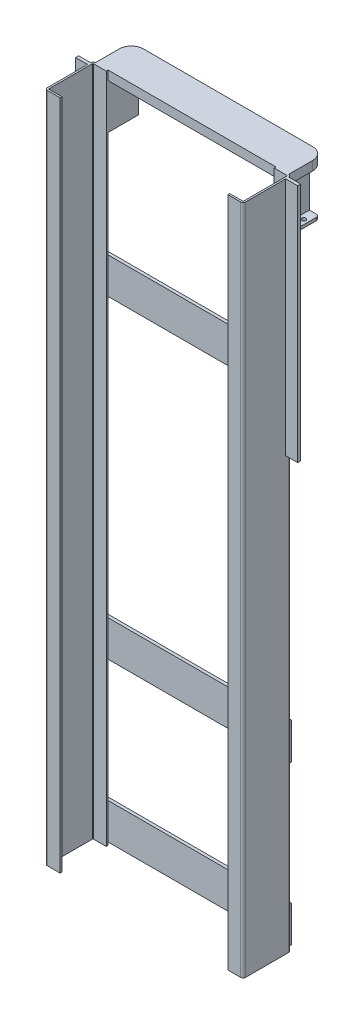
SolidWorks part; units mm, degrees
ref_plane "Front Plane" through (0, 0, 0) normal (0, 0, 1) x (1, 0, 0)
ref_plane "Top Plane" through (0, 0, 0) normal (0, 1, 0) x (1, 0, 0)
ref_plane "Right Plane" through (0, 0, 0) normal (1, 0, 0) x (0, 0, -1)
sketch "Sketch1" plane through (0, 0, 0) normal (0, 1, 0) x (1, 0, 0)
  line L0 (0, 0) -> (413, 0) construction
  line L1 (350, 100) -> (403, 100)
  line L2 (413, 90) -> (413, -90)
  line L3 (403, -100) -> (350, -100)
  arc A0 (413, -90) -> (403, -100) centre (403, -90) cw
  arc A1 (403, 100) -> (413, 90) centre (403, 90) cw
  point P9 (413, -100)
  point P12 (413, 100)
  dimension "D4" = 10
  dimension "D1" = 413
  dimension "D2" = 200
  dimension "D3" = 63
extrude "Extrude-Thin1" add sketch "Sketch1" along normal mid plane 2800 thin
sketch "Sketch2" plane through (0, 1400, 0) normal (0, 1, 0) x (1, 0, 0)
  line L1 (413, 90) -> (463, 90)
  line L2 (413, 90) -> (413, 77.5)
  line L3 (413, 77.5) -> (463, 77.5)
  line L4 (463, 90) -> (463, 77.5)
  dimension "D1" = 50
  dimension "D2" = 12.5
extrude "Boss-Extrude1" add sketch "Sketch2" against normal blind 1000
mirror "Mirror1" about plane through (0, 0, 0) normal (1, 0, 0) of bodies 102
sketch "Sketch4" plane through (0, 1400, 0) normal (0, 1, 0) x (1, 0, 0)
  line L1 (-403, 100) -> (403, 100)
  line L2 (-403, 100) -> (-403, 200)
  line L3 (-353, 250) -> (353, 250)
  line L4 (403, 100) -> (403, 200)
  arc A0 (-403, 200) -> (-353, 250) centre (-353, 200) cw
  arc A1 (353, 250) -> (403, 200) centre (353, 200) cw
  point P9 (403, 250)
  dimension "D2" = 50
  dimension "D1" = 150
extrude "Boss-Extrude2" add sketch "Sketch4" against normal blind 38
sketch "Sketch5" plane through (0, 0, -100) normal (0, 0, -1) x (-1, 0, 0)
  line L0 (-403, 1362) -> (-403, -1400) construction
  line L1 (-403, -1387.5) -> (403, -1387.5)
  line L2 (-403, -1387.5) -> (-403, -1237.5)
  line L3 (-403, -1237.5) -> (403, -1237.5)
  line L4 (403, -1387.5) -> (403, -1237.5)
  line L5 (403, 1362) -> (403, -1400) construction
  line L6 (350, -1400) -> (403, -1400) construction
  dimension "D1" = 12.5
  dimension "D2" = 150
extrude "Boss-Extrude3" add sketch "Sketch5" along normal blind 12.5
pattern_linear "LPattern1" count 2 spacing 660 along (0, 1, 0) of "Boss-Extrude3"
pattern_linear "LPattern2" count 2 spacing 1970 along (0, 1, 0) of "Boss-Extrude3"
sketch "Sketch6" plane through (0, 1362, 0) normal (0, -1, 0) x (1, 0, 0)
  line L1 (350, -100) -> (362.5, -100)
  line L2 (350, -100) -> (350, -227)
  line L3 (350, -227) -> (362.5, -227)
  line L4 (362.5, -100) -> (362.5, -227)
  dimension "D1" = 127
  dimension "D2" = 12.5
extrude "Boss-Extrude4" add sketch "Sketch6" along normal blind 175
sketch "Sketch7" plane through (0, 1187, 0) normal (0, -1, 0) x (1, 0, 0)
  line L0 (350, -227) -> (362.5, -227) construction
  line L1 (350, -100) -> (403, -100)
  line L2 (350, -100) -> (350, -227)
  line L3 (350, -227) -> (403, -227)
  line L4 (403, -100) -> (403, -227)
  circle A0 centre (384, -182) radius 8.75
  dimension "D1" = 17.5
  dimension "D2" = 19
  dimension "D3" = 82
extrude "Boss-Extrude5" add sketch "Sketch7" along normal blind 12.5
fillet "Fillet1" radius 12.5 1 edges at (403, 1180.75, -227)
mirror "Mirror2" about plane through (0, 0, 0) normal (1, 0, 0) of "Boss-Extrude4", "Boss-Extrude5", "Fillet1"
